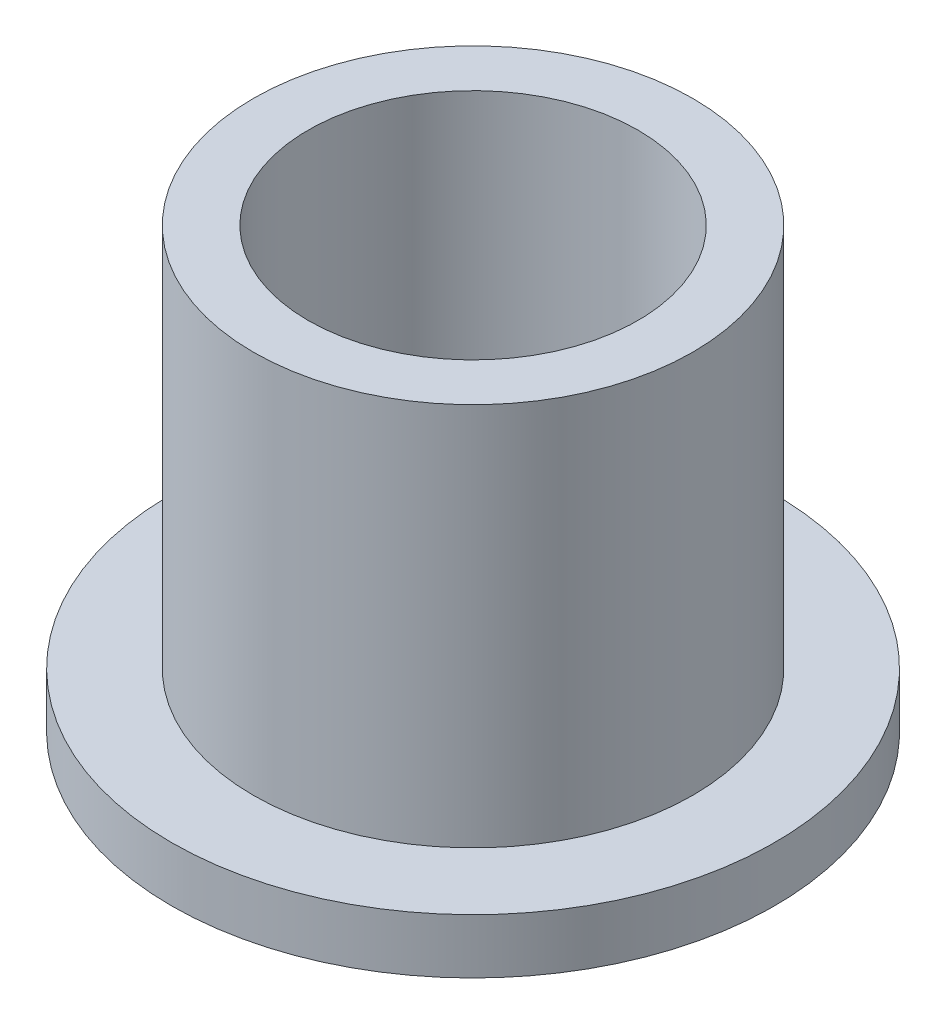
SolidWorks part; units mm, degrees
ref_plane "Front" through (0, 0, 0) normal (0, 0, 1) x (1, 0, 0)
ref_plane "Top" through (0, 0, 0) normal (0, 1, 0) x (1, 0, 0)
ref_plane "Right" through (0, 0, 0) normal (1, 0, 0) x (0, 0, -1)
sketch "Sketch1" plane through (0, 0, 0) normal (0, 1, 0) x (1, 0, 0)
  circle A0 centre (0, 0) radius 4.7752
  circle A1 centre (0, 0) radius 6.3627
  circle A2 centre (0, 0) radius 8.7312
  dimension "ID" = 9.5504
  dimension "OD" = 12.7254
  dimension "FlangeOD" = 17.4625
sketch "Sketch2" plane through (0, 0, 0) normal (0, 1, 0) x (1, 0, 0)
  circle A0 centre (0, 0) radius 4.7752 construction
  circle A1 centre (0, 0) radius 6.3627 construction
  circle A2 centre (0, 0) radius 4.7752
  circle A3 centre (0, 0) radius 6.3627
extrude "Boss-Extrude1" add sketch "Sketch2" along normal blind 12.7
sketch "Sketch3" plane through (0, 0, 0) normal (0, 1, 0) x (1, 0, 0)
  circle A0 centre (0, 0) radius 8.7312 construction
  circle A1 centre (0, 0) radius 6.3627 construction
  circle A2 centre (0, 0) radius 8.7312
  circle A3 centre (0, 0) radius 6.3627
extrude "Boss-Extrude2" add sketch "Sketch3" along normal blind 1.5875
